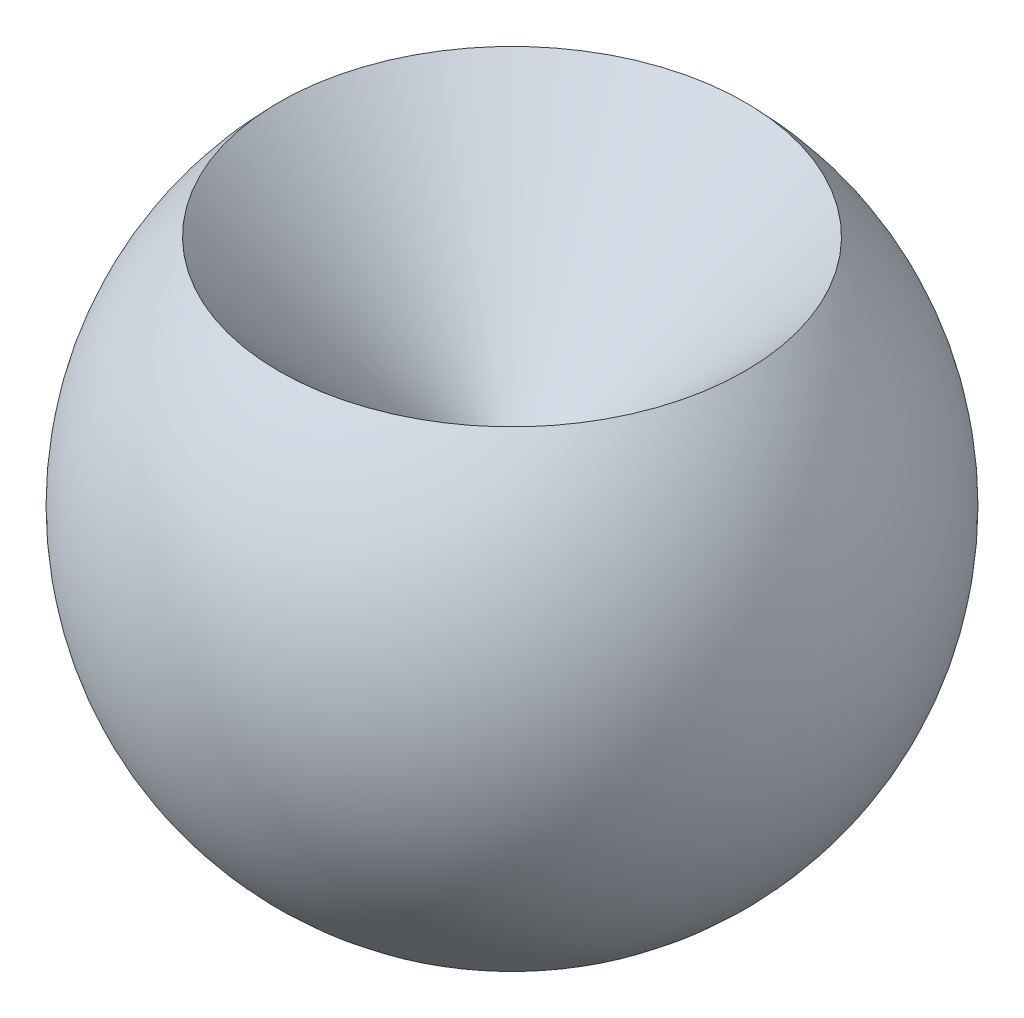
SolidWorks part; units mm, degrees
ref_plane "Front Plane" through (0, 0, 0) normal (0, 0, 1) x (1, 0, 0)
ref_plane "Top Plane" through (0, 0, 0) normal (0, 1, 0) x (1, 0, 0)
ref_plane "Right Plane" through (0, 0, 0) normal (1, 0, 0) x (0, 0, -1)
sketch "Sketch1" plane through (0, 0, 0) normal (0, 0, 1) x (1, 0, 0)
  line L0 (0, 0) -> (0, -5)
  line L1 (0, 0) -> (3.5355, 3.5355)
  arc A0 (0, -5) -> (3.5355, 3.5355) centre (0, 0) ccw
  dimension "D1" = 10
  dimension "D2" = 135
revolve "Revolve1" add sketch "Sketch1" angle 360 about L0
